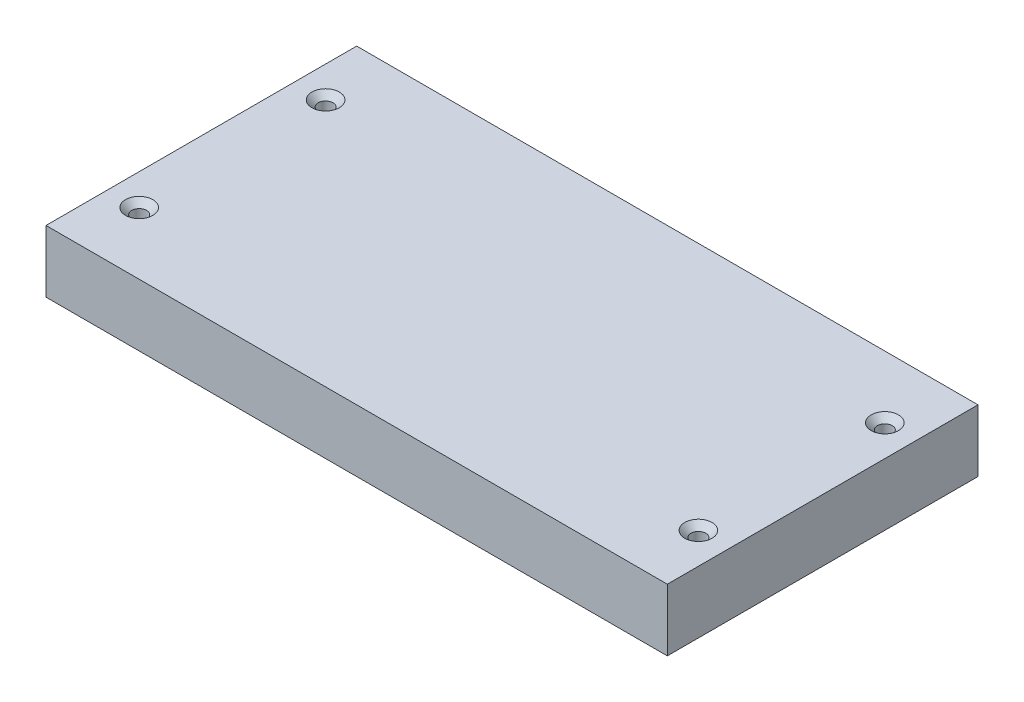
SolidWorks part; units mm, degrees
ref_plane "Front Plane" through (0, 0, 0) normal (0, 0, 1) x (1, 0, 0)
ref_plane "Top Plane" through (0, 0, 0) normal (0, 1, 0) x (1, 0, 0)
ref_plane "Right Plane" through (0, 0, 0) normal (1, 0, 0) x (0, 0, -1)
sketch "Sketch1" plane through (0, 0, 0) normal (0, 1, 0) x (1, 0, 0)
  line L0 (-50, 0) -> (0, 0) construction
  line L1 (-50, 25) -> (50, 25)
  line L2 (-50, 25) -> (-50, -25)
  line L3 (-50, -25) -> (50, -25)
  line L4 (50, 25) -> (50, -25)
  line L5 (0, 0) -> (0, 25) construction
  dimension "D1" = 50
  dimension "D2" = 100
extrude "Boss-Extrude1" add sketch "Sketch1" along normal blind 10
sketch "Sketch3" plane through (0, 10, 0) normal (0, 1, 0) x (1, 0, 0)
  line L0 (-50, 25) -> (-50, -25) construction
  line L2 (50, 25) -> (-50, 25) construction
  line L3 (0, 0) -> (0, 30.6766) construction
  line L4 (0, 30.6766) -> (0, 0) construction
  line L5 (0, 0) -> (63.4689, 0) construction
  point P0 (-45, 15)
  point P5 (45, 15)
  point P10 (45, -15)
  point P11 (-45, -15)
  dimension "D1" = 5
  dimension "D2" = 10
hole_wizard "CSK for M2 Flat Head Machine Screw1" positions "3DSketch3" profile "Sketch5" countersink size "M2" standard "ANSI Metric" end condition through all
sketch3d "3DSketch3"
  point P0 (-45, 10, -15)
  point P3 (45, 10, -15)
  point P6 (45, 10, 15)
  point P9 (-45, 10, 15)
sketch "Sketch5" plane through (-45, 10, -15) normal (1, 0, 0) x (0, 0, 1)
  line L0 (0, 0) -> (0, 10)
  line L1 (0, 10) -> (1.2, 10)
  line L2 (1.2, 10) -> (1.2, 1)
  line L3 (1.2, 1) -> (2.2, 0)
  line L5 (2.2, 0) -> (0, 0)
  line L6 (-1.2, 1) -> (-2.2, 0) construction
  line L11 (0, -6.35) -> (0, 107.95) construction
  dimension "Thru Hole Dia." = 2.4
  dimension "Thru Hole Depth" = 10
  dimension "Near C'Sink Dia." = 4.4
  dimension "Near C'Sink Angle" = 90
